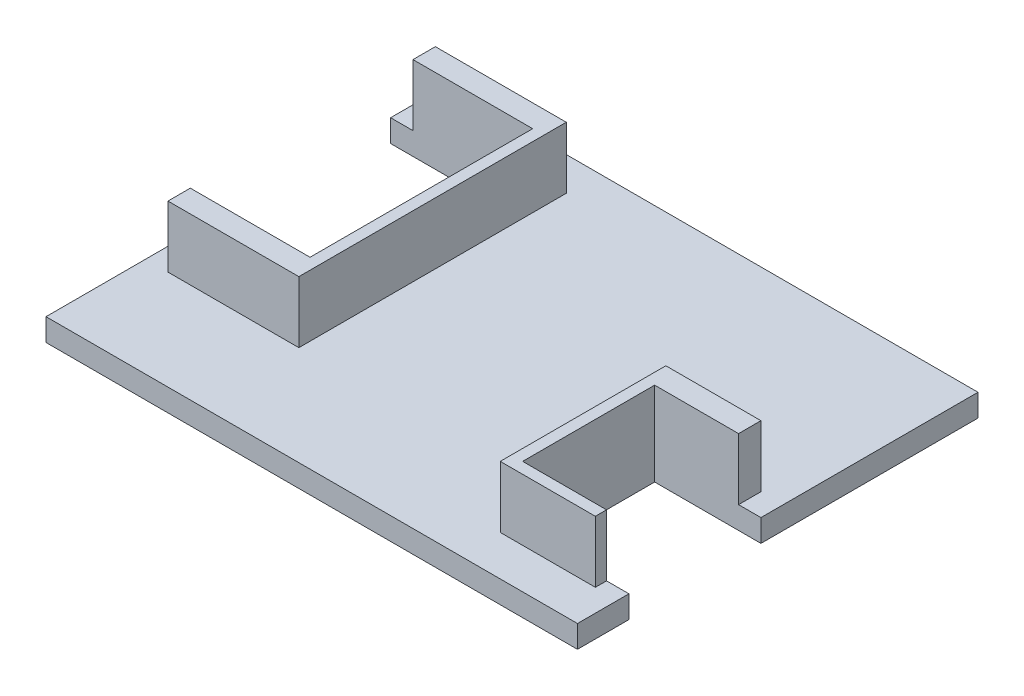
SolidWorks part; units mm, degrees
ref_plane "Plan de face" through (0, 0, 0) normal (0, 0, 1) x (1, 0, 0)
ref_plane "Plan de dessus" through (0, 0, 0) normal (0, 1, 0) x (1, 0, 0)
ref_plane "Plan de droite" through (0, 0, 0) normal (1, 0, 0) x (0, 0, -1)
sketch "Esquisse1" plane through (0, 0, 0) normal (0, 1, 0) x (1, 0, 0)
  line L1 (0, 0) -> (47.5, 0)
  line L2 (0, 0) -> (0, 35.8)
  line L3 (0, 35.8) -> (47.5, 35.8)
  line L4 (47.5, 0) -> (47.5, 35.8)
  dimension "D1" = 35.8
  dimension "D2" = 47.5
extrude "Boss.-Extru.1" add sketch "Esquisse1" along normal blind 2
sketch "Esquisse2" plane through (0, 2, 0) normal (0, 1, 0) x (1, 0, 0)
  line L0 (47.5, 0) -> (47.5, 35.8) construction
  line L1 (47.5, 16.4) -> (38, 16.4)
  line L2 (47.5, 16.4) -> (47.5, 4.6)
  line L3 (47.5, 4.6) -> (38, 4.6)
  line L4 (38, 16.4) -> (38, 4.6)
  line L5 (47.5, 35.8) -> (0, 35.8) construction
  line L6 (0, 0) -> (47.5, 0) construction
  dimension "D1" = 19.4
  dimension "D2" = 4.6
  dimension "D3" = 9.5
extrude "Enlèv. mat.-Extru.1" cut sketch "Esquisse2" against normal blind 10
sketch "Esquisse3" plane through (0, 2, 0) normal (0, 1, 0) x (1, 0, 0)
  line L0 (0, 35.8) -> (0, 0) construction
  line L1 (0, 30.8) -> (12.7, 30.8)
  line L2 (0, 30.8) -> (0, 10.9)
  line L3 (0, 10.9) -> (12.7, 10.9)
  line L4 (12.7, 30.8) -> (12.7, 10.9)
  line L5 (0, 0) -> (47.5, 0) construction
  line L6 (47.5, 35.8) -> (0, 35.8) construction
  dimension "D1" = 10.9
  dimension "D2" = 5
  dimension "D3" = 12.7
extrude "Enlèv. mat.-Extru.2" cut sketch "Esquisse3" against normal blind 10
sketch "Esquisse5" plane through (0, 2, 0) normal (0, 1, 0) x (1, 0, 0)
  line L0 (38, 16.4) -> (38, 4.6) construction
  line L1 (38, 16.4) -> (37, 16.4)
  line L2 (38, 16.4) -> (38, 4.6)
  line L3 (38, 4.6) -> (37, 4.6)
  line L4 (37, 16.4) -> (37, 4.6)
  dimension "D1" = 1
  dimension "D2" = 0
  dimension "D3" = 0
extrude "Boss.-Extru.2" add sketch "Esquisse5" along normal blind 5.5
sketch "Esquisse6" plane through (0, 2, 0) normal (0, 1, 0) x (1, 0, 0)
  line L0 (38, 4.6) -> (47.5, 4.6) construction
  line L1 (37, 4.6) -> (45.5, 4.6)
  line L2 (37, 4.6) -> (37, 3.6)
  line L3 (37, 3.6) -> (45.5, 3.6)
  line L4 (45.5, 4.6) -> (45.5, 3.6)
  line L5 (47.5, 0) -> (47.5, 4.6) construction
  dimension "D1" = 0
  dimension "D2" = 2
  dimension "D3" = 0
  dimension "D4" = 1
extrude "Boss.-Extru.3" add sketch "Esquisse6" along normal blind 5.5
sketch "Esquisse7" plane through (0, 2, 0) normal (0, 1, 0) x (1, 0, 0)
  line L0 (47.5, 16.4) -> (38, 16.4) construction
  line L1 (37, 18.4) -> (45.5, 18.4)
  line L2 (37, 18.4) -> (37, 16.4)
  line L3 (37, 16.4) -> (45.5, 16.4)
  line L4 (45.5, 18.4) -> (45.5, 16.4)
  line L5 (47.5, 16.4) -> (47.5, 35.8) construction
  dimension "D1" = 0
  dimension "D2" = 0
  dimension "D3" = 2
  dimension "D4" = 2
extrude "Boss.-Extru.4" add sketch "Esquisse7" along normal blind 5.5
sketch "Esquisse8" plane through (0, 2, 0) normal (0, 1, 0) x (1, 0, 0)
  line L0 (12.7, 30.8) -> (0, 30.8) construction
  line L1 (2, 32.8) -> (12.7, 32.8)
  line L2 (2, 32.8) -> (2, 30.8)
  line L3 (2, 30.8) -> (12.7, 30.8)
  line L4 (12.7, 32.8) -> (12.7, 30.8)
  line L5 (0, 35.8) -> (0, 30.8) construction
  dimension "D1" = 0
  dimension "D2" = 2
  dimension "D3" = 0
  dimension "D4" = 2
extrude "Boss.-Extru.5" add sketch "Esquisse8" along normal blind 5.5
sketch "Esquisse9" plane through (0, 2, 0) normal (0, 1, 0) x (1, 0, 0)
  line L0 (12.7, 10.9) -> (12.7, 30.8) construction
  line L1 (12.7, 32.8) -> (13.7, 32.8)
  line L2 (12.7, 32.8) -> (12.7, 10.9)
  line L3 (12.7, 10.9) -> (13.7, 10.9)
  line L4 (13.7, 32.8) -> (13.7, 10.9)
  dimension "D1" = 0
  dimension "D2" = 0
  dimension "D3" = 1
extrude "Boss.-Extru.6" add sketch "Esquisse9" along normal blind 5.5
sketch "Esquisse11" plane through (0, 2, 0) normal (0, 1, 0) x (1, 0, 0)
  line L0 (0, 10.9) -> (12.7, 10.9) construction
  line L1 (2, 10.9) -> (13.7, 10.9)
  line L2 (2, 10.9) -> (2, 8.9)
  line L3 (2, 8.9) -> (13.7, 8.9)
  line L4 (13.7, 10.9) -> (13.7, 8.9)
  line L5 (0, 10.9) -> (0, 0) construction
  dimension "D1" = 0
  dimension "D2" = 2
  dimension "D3" = 2
extrude "Boss.-Extru.7" add sketch "Esquisse11" along normal blind 5.5
